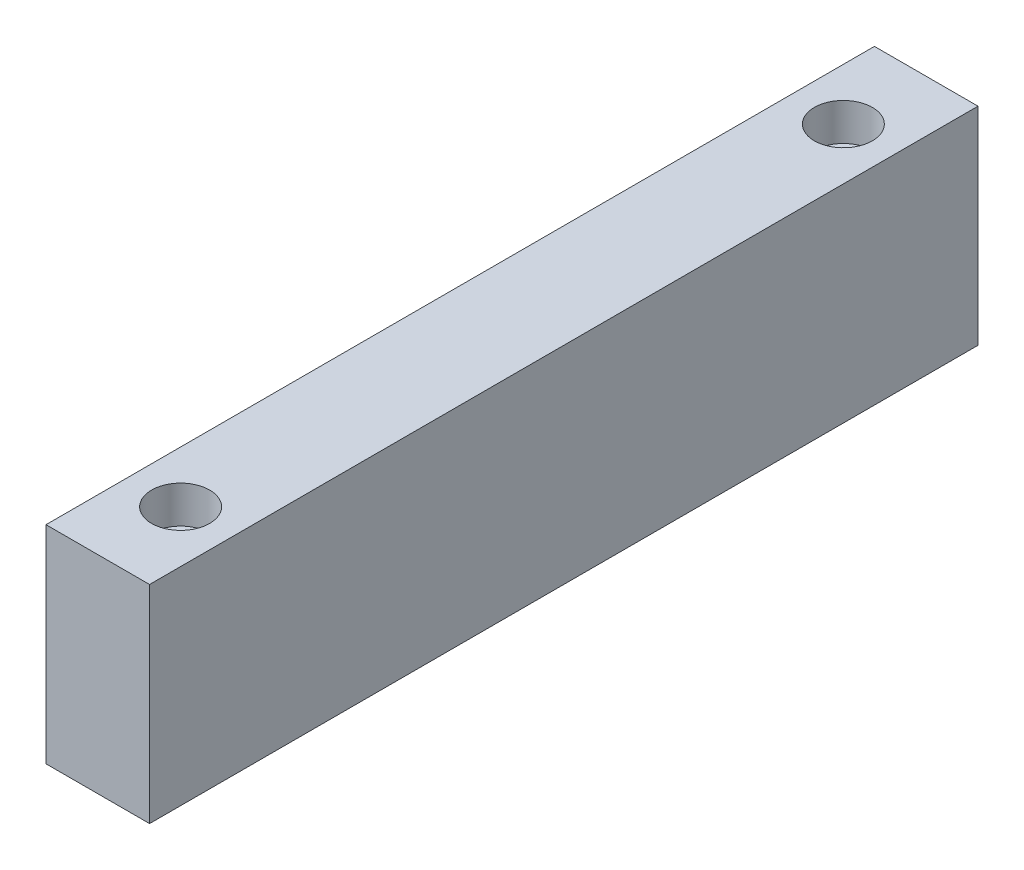
SolidWorks part; units mm, degrees
ref_plane "Front" through (0, 0, 0) normal (0, 0, 1) x (1, 0, 0)
ref_plane "Top" through (0, 0, 0) normal (0, 1, 0) x (1, 0, 0)
ref_plane "Right" through (0, 0, 0) normal (1, 0, 0) x (0, 0, -1)
sketch "Sketch1" plane through (0, 0, 0) normal (1, 0, 0) x (0, 0, -1)
  line L0 (0, -5.5448) -> (0, 65.954) construction
  line L1 (-100, 50) -> (100, 50)
  line L2 (-100, 50) -> (-100, 0)
  line L3 (-100, 0) -> (100, 0)
  line L4 (100, 50) -> (100, 0)
  dimension "D1" = 200
  dimension "D2" = 50
extrude "Boss-Extrude1" add sketch "Sketch1" along normal blind 25
hole_wizard "CBORE for M8 Socket Head Cap Screw1" positions "Sketch3" profile "Sketch4" counterbore size "M8" standard "JIS" end condition through all
sketch "Sketch3" plane through (0, 50, 0) normal (0, 1, 0) x (-1, 0, 0)
  line L0 (6.7242, 0) -> (-36.5302, 0) construction
  line L2 (0, -100) -> (0, 100) construction
  point P0 (-12.5, 80)
  point P1 (-12.5, -80)
  dimension "D1" = 160
  dimension "D2" = 12.5
sketch "Sketch4" plane through (12.5, 50, 80) normal (1, 0, 0) x (0, 0, 1)
  line L0 (0, 0) -> (0, 50)
  line L1 (0, 50) -> (4.5, 50)
  line L3 (4.5, 50) -> (4.5, 9)
  line L4 (4.5, 9) -> (7, 9)
  line L5 (7, 9) -> (7, 0)
  line L7 (7, 0) -> (0, 0)
  line L11 (0, -6.35) -> (0, 107.95) construction
  dimension "Thru Hole Dia." = 9
  dimension "Thru Hole Depth" = 50
  dimension "C'Bore Dia." = 14
  dimension "C'Bore Depth" = 9
